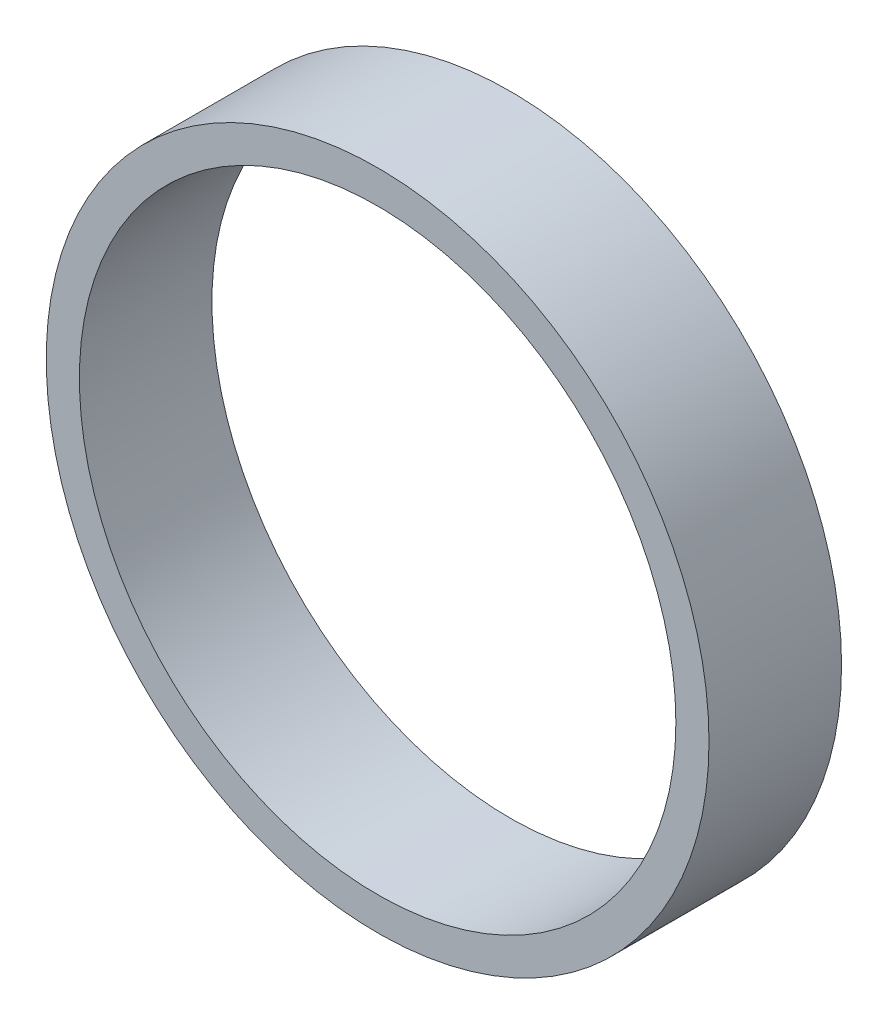
SolidWorks part; units mm, degrees
ref_plane "Front Plane" through (0, 0, 0) normal (0, 0, 1) x (1, 0, 0)
ref_plane "Top Plane" through (0, 0, 0) normal (0, 1, 0) x (1, 0, 0)
ref_plane "Right Plane" through (0, 0, 0) normal (1, 0, 0) x (0, 0, -1)
sketch "Sketch1" plane through (0, 0, 0) normal (0, 0, 1) x (1, 0, 0)
  circle A0 centre (0, 0) radius 31.75
  circle A1 centre (0, 0) radius 28.575
  dimension "D1" = 63.5
  dimension "D2" = 57.15
extrude "Boss-Extrude1" add sketch "Sketch1" along normal blind 12.7
